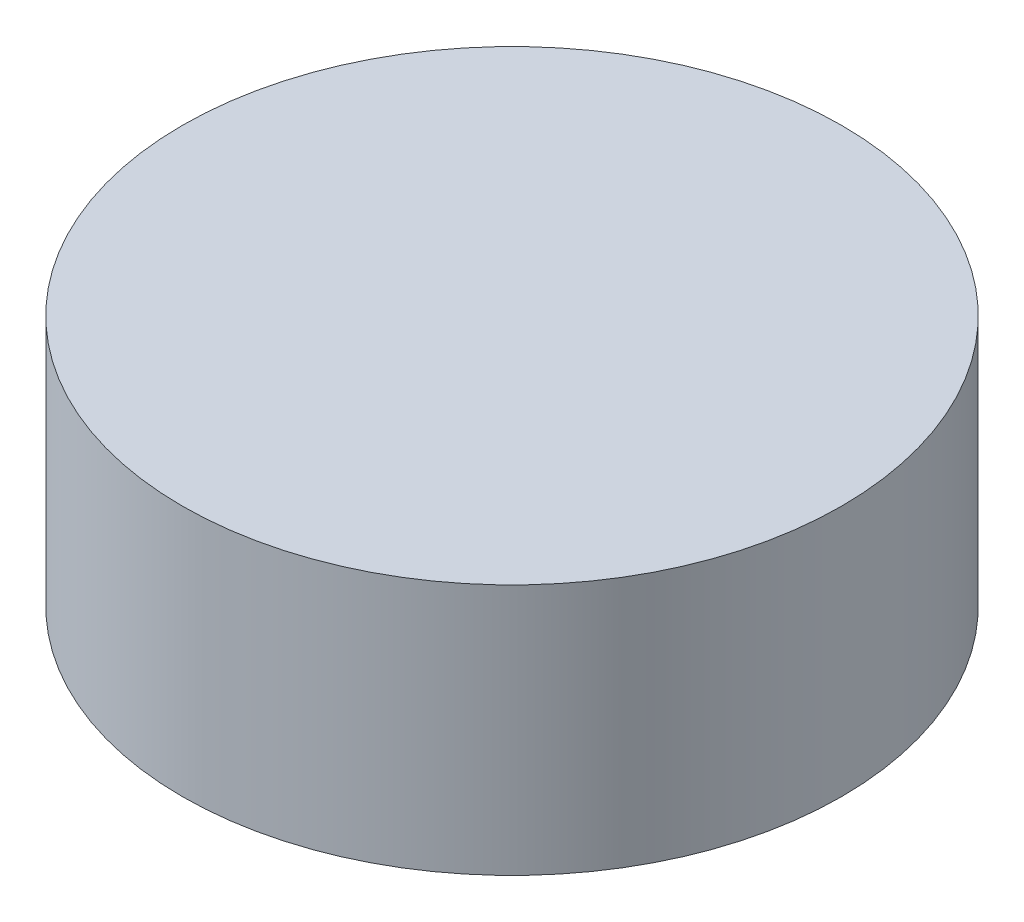
SolidWorks part; units mm, degrees
ref_plane "Front Plane" through (0, 0, 0) normal (0, 0, 1) x (1, 0, 0)
ref_plane "Top Plane" through (0, 0, 0) normal (0, 1, 0) x (1, 0, 0)
ref_plane "Right Plane" through (0, 0, 0) normal (1, 0, 0) x (0, 0, -1)
sketch "Sketch1" plane through (0, 0, 0) normal (0, 1, 0) x (1, 0, 0)
  circle A0 centre (0, 0) radius 19
  dimension "D1" = 38
extrude "Boss-Extrude1" add sketch "Sketch1" along normal blind 14.5
